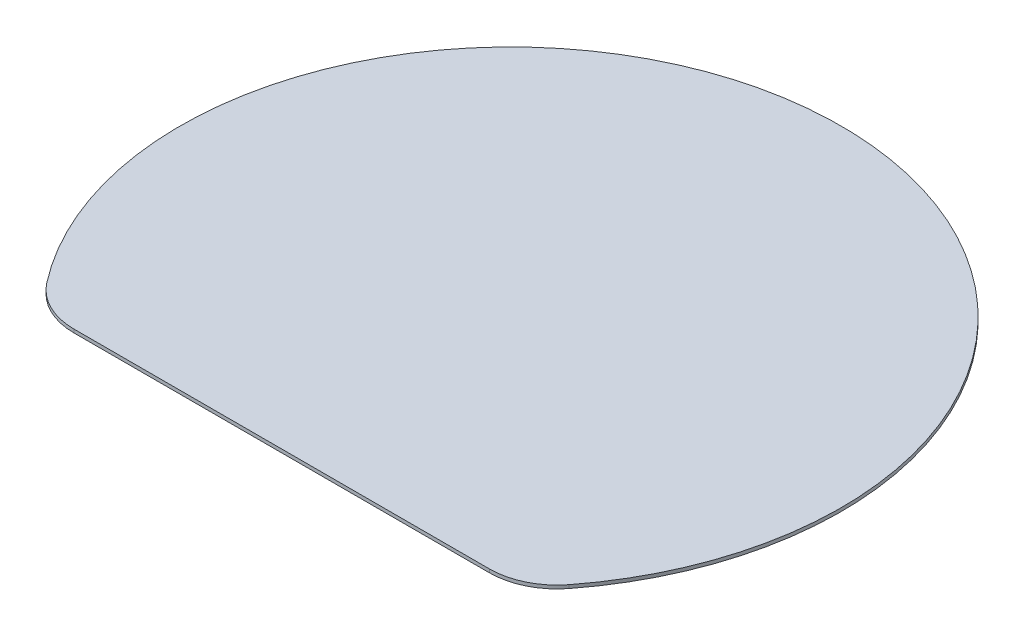
SolidWorks part; units mm, degrees
ref_plane "Front Plane" through (0, 0, 0) normal (0, 0, 1) x (1, 0, 0)
ref_plane "Top Plane" through (0, 0, 0) normal (0, 1, 0) x (1, 0, 0)
ref_plane "Right Plane" through (0, 0, 0) normal (1, 0, 0) x (0, 0, -1)
sketch "Sketch1" plane through (0, 0, 0) normal (0, 1, 0) x (1, 0, 0)
  line L0 (-140.7125, -135) -> (140.7125, -135)
  arc A0 (140.7125, -135) -> (-140.7125, -135) centre (0, 0) ccw
  point P1 (0, -135)
  dimension "D1" = 390
  dimension "D2" = 135
extrude "Boss-Extrude1" add sketch "Sketch1" along normal blind 2
fillet "Fillet1" radius 40 2 edges at (-140.7125, 1, 135) (140.7125, 1, 135)
